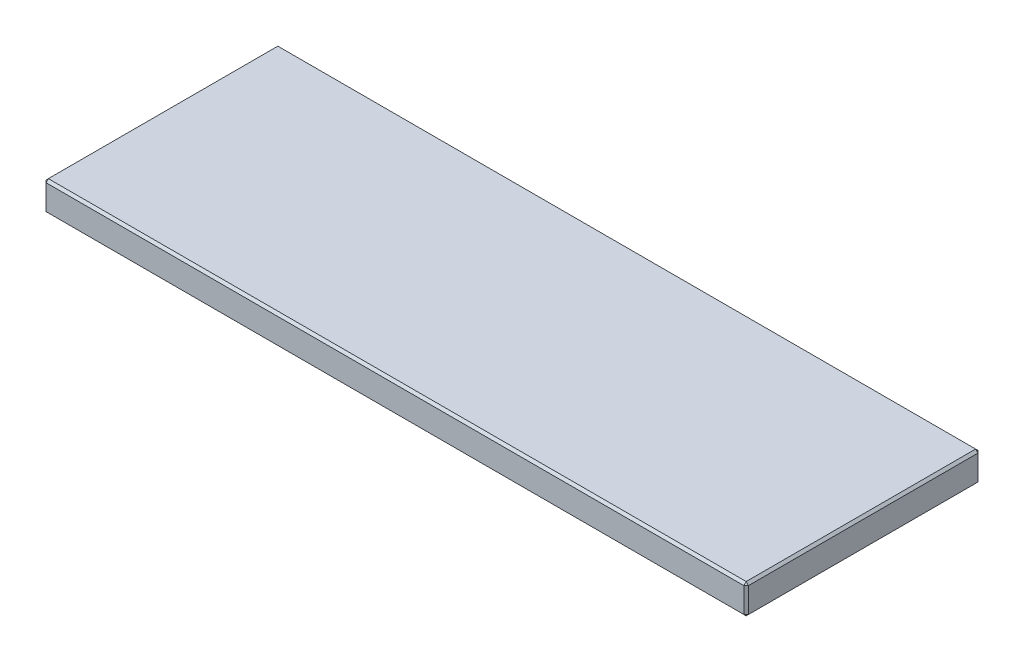
SolidWorks part; units mm, degrees
ref_plane "Front Plane" through (0, 0, 0) normal (0, 0, 1) x (1, 0, 0)
ref_plane "Top Plane" through (0, 0, 0) normal (0, 1, 0) x (1, 0, 0)
ref_plane "Right Plane" through (0, 0, 0) normal (1, 0, 0) x (0, 0, -1)
sketch "Sketch1" plane through (0, 0, 0) normal (0, 1, 0) x (1, 0, 0)
  line L1 (-37.5, -12.5) -> (37.5, -12.5)
  line L2 (-37.5, -12.5) -> (-37.5, 12.5)
  line L3 (-37.5, 12.5) -> (37.5, 12.5)
  line L4 (37.5, -12.5) -> (37.5, 12.5)
  line L5 (-37.5, -12.5) -> (37.5, 12.5) construction
  line L6 (-37.5, 12.5) -> (37.5, -12.5) construction
  point P0 (0, 0)
  dimension "D1" = 25
  dimension "D2" = 75
extrude "Boss-Extrude1" add sketch "Sketch1" along normal blind 3.175
chamfer "Chamfer1" distance 0.25 angle 45 12 edges at (37.5, 0, 0) (37.5, 1.5875, -12.5) (0, 0, -12.5) (-37.5, 1.5875, -12.5) (-37.5, 0, 0) (-37.5, 3.175, 0) (0, 3.175, -12.5) (37.5, 3.175, 0) (-37.5, 1.5875, 12.5) (0, 3.175, 12.5) (37.5, 1.5875, 12.5) (0, 0, 12.5)
